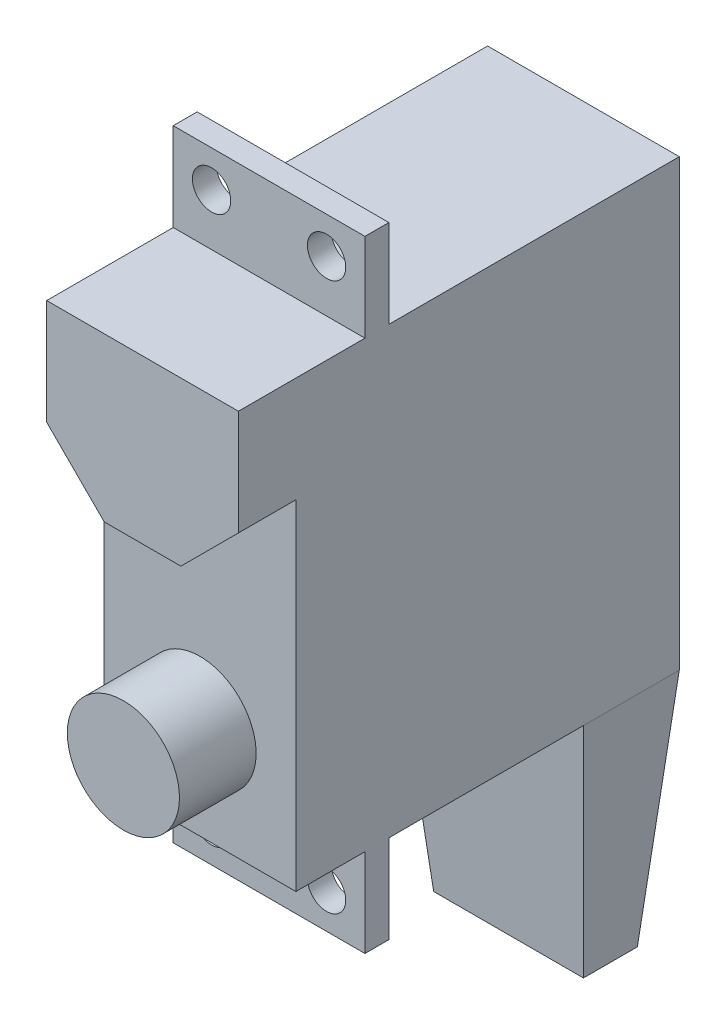
SolidWorks part; units mm, degrees
ref_plane "Front Plane" through (0, 0, 0) normal (1, 0, 0) x (0, 1, 0)
ref_plane "Top Plane" through (0, 0, 0) normal (0, 0, 1) x (0, 1, 0)
ref_plane "Right Plane" through (0, 0, 0) normal (0, 1, 0) x (-1, 0, 0)
sketch "Sketch1" plane through (0, 0, 0) normal (0, 0, 1) x (0, 1, 0)
  line L1 (0, 0) -> (23.2, 0)
  line L2 (0, 0) -> (0, 10)
  line L3 (0, 10) -> (23.2, 10)
  line L4 (23.2, 0) -> (23.2, 10)
  dimension "D1" = 23.2
  dimension "D2" = 10
extrude "Boss-Extrude1" add sketch "Sketch1" along normal blind 20
sketch "Sketch2" plane through (0, 0, 20) normal (0, 0, 1) x (1, 0, 0)
  line L0 (0, 0) -> (0, 23.2) construction
  line L1 (-10, 23.2) -> (0, 23.2)
  line L2 (-10, 23.2) -> (-10, 14.7)
  line L3 (-10, 14.7) -> (0, 14.7)
  line L4 (0, 23.2) -> (0, 14.7)
  dimension "D1" = 8.5
extrude "Boss-Extrude2" add sketch "Sketch2" along normal blind 3
chamfer "Chamfer1" distance 3 angle 45 2 edges at (-10, 14.7, 21.5) (0, 14.7, 21.5)
sketch "Sketch3" plane through (0, 0, 20) normal (0, 0, 1) x (1, 0, 0)
  line L0 (-10, 0) -> (0, 0) construction
  line L1 (-10, 0) -> (0, 0) construction
  circle A0 centre (-5, 5.2) radius 2.925
  point P2 (0, 0)
  point P5 (-5, 0)
  dimension "D2" = 5.85
  dimension "D1" = 5.2
extrude "Boss-Extrude3" add sketch "Sketch3" along normal blind 4
sketch "Sketch5" plane through (0, 0, 20) normal (0, 0, 1) x (1, 0, 0)
  line L0 (-10, 23.2) -> (-10, 0) construction
  line L1 (-10, 27.8) -> (0, 27.8)
  line L2 (-10, 27.8) -> (-10, -4.6)
  line L3 (-10, -4.6) -> (0, -4.6)
  line L4 (0, 27.8) -> (0, -4.6)
  line L5 (0, 0) -> (0, 17.7) construction
  point P5 (-10, 11.6)
  point P6 (-10, 11.6)
  point P11 (0, 11.6)
  dimension "D1" = 32.4
extrude "Boss-Extrude4" add sketch "Sketch5" against normal blind 1.25 from offset 3.6 offset against normal yes
sketch "Sketch6" plane through (0, 0, 16.4) normal (0, 0, 1) x (1, 0, 0)
  line L0 (-10, 0) -> (-10, -4.6) construction
  line L1 (0, -4.6) -> (0, 0) construction
  line L3 (0, 27.8) -> (-10, 27.8) construction
  circle A0 centre (-8, -2.7) radius 1
  circle A1 centre (-5, 5.2) radius 2.925 construction
  circle A2 centre (-2, -2.7) radius 1
  circle A3 centre (-8, 25.9) radius 1
  circle A4 centre (-2, 25.9) radius 1
  dimension "D1" = 7.9
  dimension "D2" = 2
  dimension "D3" = 2
  dimension "D4" = 2
  dimension "D5" = 1.9
extrude "Cut-Extrude1" cut sketch "Sketch6" against normal blind 1.25
sketch "Sketch7" plane through (0, 0, 0) normal (0, -1, 0) x (1, 0, 0)
  line L0 (-10, 15.15) -> (-10, 0) construction
  line L1 (0, 0) -> (-10, 0)
  line L2 (0, 0) -> (0, 5)
  line L3 (0, 5) -> (-10, 5)
  line L4 (-10, 0) -> (-10, 5)
  dimension "D1" = 5
extrude "Boss-Extrude5" add sketch "Sketch7" along normal blind 12.5 draft 5
